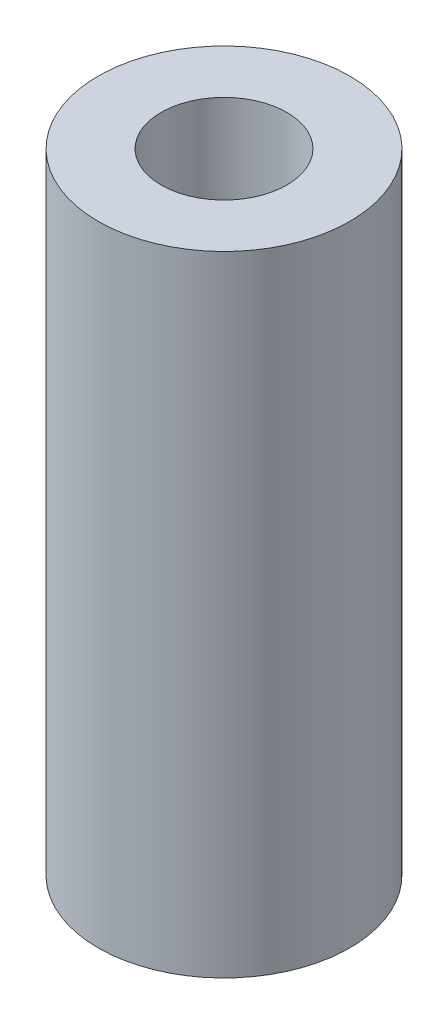
SolidWorks part; units mm, degrees
ref_plane "Front Plane" through (0, 0, 0) normal (0, 0, 1) x (1, 0, 0)
ref_plane "Top Plane" through (0, 0, 0) normal (0, 1, 0) x (1, 0, 0)
ref_plane "Right Plane" through (0, 0, 0) normal (1, 0, 0) x (0, 0, -1)
sketch "Sketch1" plane through (0, 0, 0) normal (0, 1, 0) x (1, 0, 0)
  circle A0 centre (0, 0) radius 1
  circle A1 centre (0, 0) radius 0.5
  dimension "D1" = 2
  dimension "D2" = 1
extrude "Boss-Extrude1" add sketch "Sketch1" along normal blind 5
